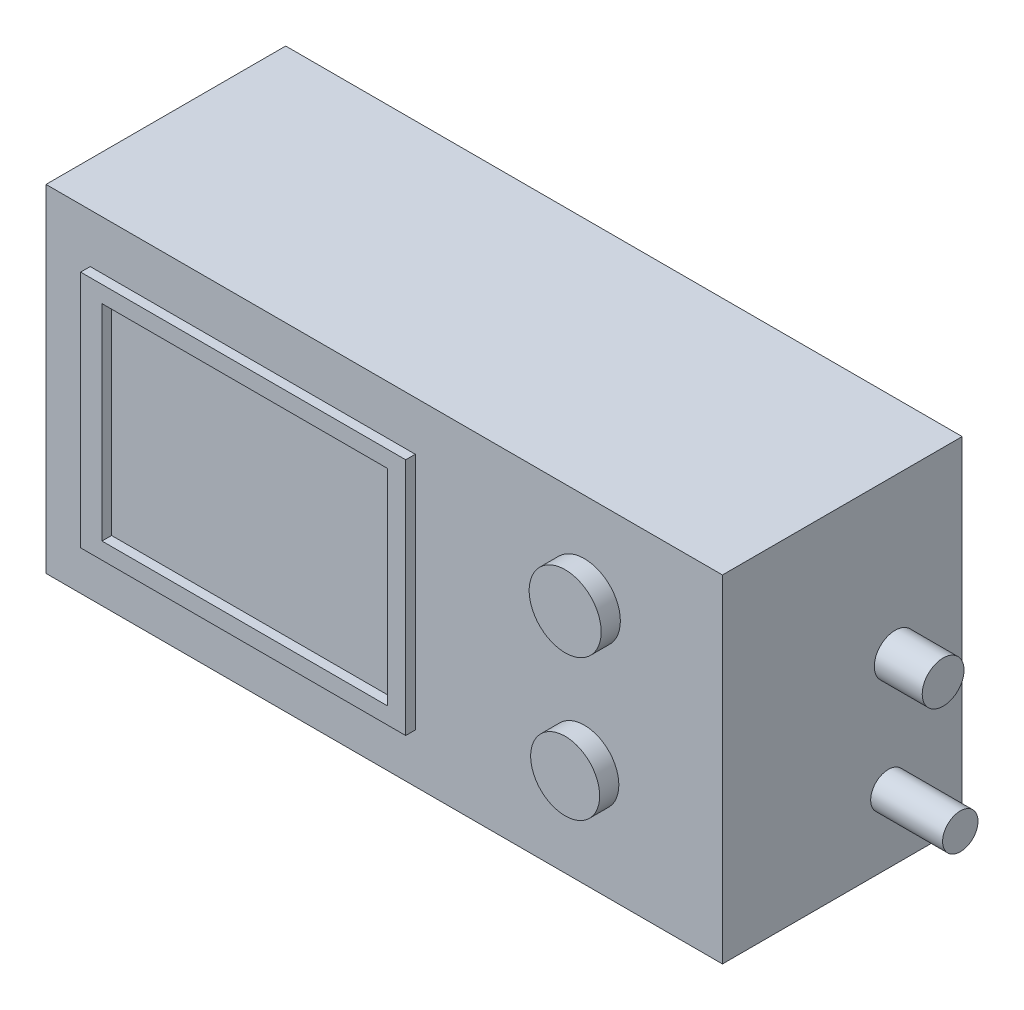
SolidWorks part; units mm, degrees
ref_plane "Front Plane" through (0, 0, 0) normal (0, 0, 1) x (1, 0, 0)
ref_plane "Top Plane" through (0, 0, 0) normal (0, 1, 0) x (1, 0, 0)
ref_plane "Right Plane" through (0, 0, 0) normal (1, 0, 0) x (0, 0, -1)
sketch "Sketch1" plane through (0, 0, 0) normal (0, 0, 1) x (1, 0, 0)
  line L1 (-70.5522, 35.1396) -> (70.5522, 35.1396)
  line L2 (-70.5522, 35.1396) -> (-70.5522, -35.1396)
  line L3 (-70.5522, -35.1396) -> (70.5522, -35.1396)
  line L4 (70.5522, 35.1396) -> (70.5522, -35.1396)
  line L5 (-70.5522, 35.1396) -> (70.5522, -35.1396) construction
  line L6 (-70.5522, -35.1396) -> (70.5522, 35.1396) construction
  point P0 (0, 0)
extrude "Boss-Extrude1" add sketch "Sketch1" along normal blind 50
sketch "Sketch2" plane through (0, 0, 50) normal (0, 0, 1) x (1, 0, 0)
  line L1 (-61.3307, 24.9076) -> (6.4748, 24.9076)
  line L2 (-61.3307, 24.9076) -> (-61.3307, -24.9076)
  line L3 (-61.3307, -24.9076) -> (6.4748, -24.9076)
  line L4 (6.4748, 24.9076) -> (6.4748, -24.9076)
  line L7 (-56.8743, 21.4471) -> (2.7186, 21.4471)
  line L8 (-56.8743, 21.4471) -> (-56.8743, -21.4471)
  line L9 (-56.8743, -21.4471) -> (2.7186, -21.4471)
  line L10 (2.7186, 21.4471) -> (2.7186, -21.4471)
  point P0 (-27.428, 0)
  point P7 (-27.428, 0)
extrude "Boss-Extrude2" add sketch "Sketch2" along normal blind 2
sketch "Sketch3" plane through (0, 0, 50) normal (0, 0, 1) x (1, 0, 0)
  circle A0 centre (41.7432, 16.1797) radius 7.5097
  circle A1 centre (41.7432, -13.5923) radius 7.1947
  point P4 (41.7432, -13.5923)
  point P5 (41.7432, 16.1797)
extrude "Boss-Extrude3" add sketch "Sketch3" along normal blind 4
sketch "Sketch4" plane through (70.5522, 0, 0) normal (1, 0, 0) x (0, 0, -1)
  circle A0 centre (-13.9698, 2.7695) radius 4.3646
extrude "Boss-Extrude4" add sketch "Sketch4" along normal blind 10
sketch "Sketch5" plane through (70.5522, 0, 0) normal (1, 0, 0) x (0, 0, -1)
  circle A0 centre (-15.3903, -20.9817) radius 3.6937
extrude "Boss-Extrude5" add sketch "Sketch5" along normal blind 15
